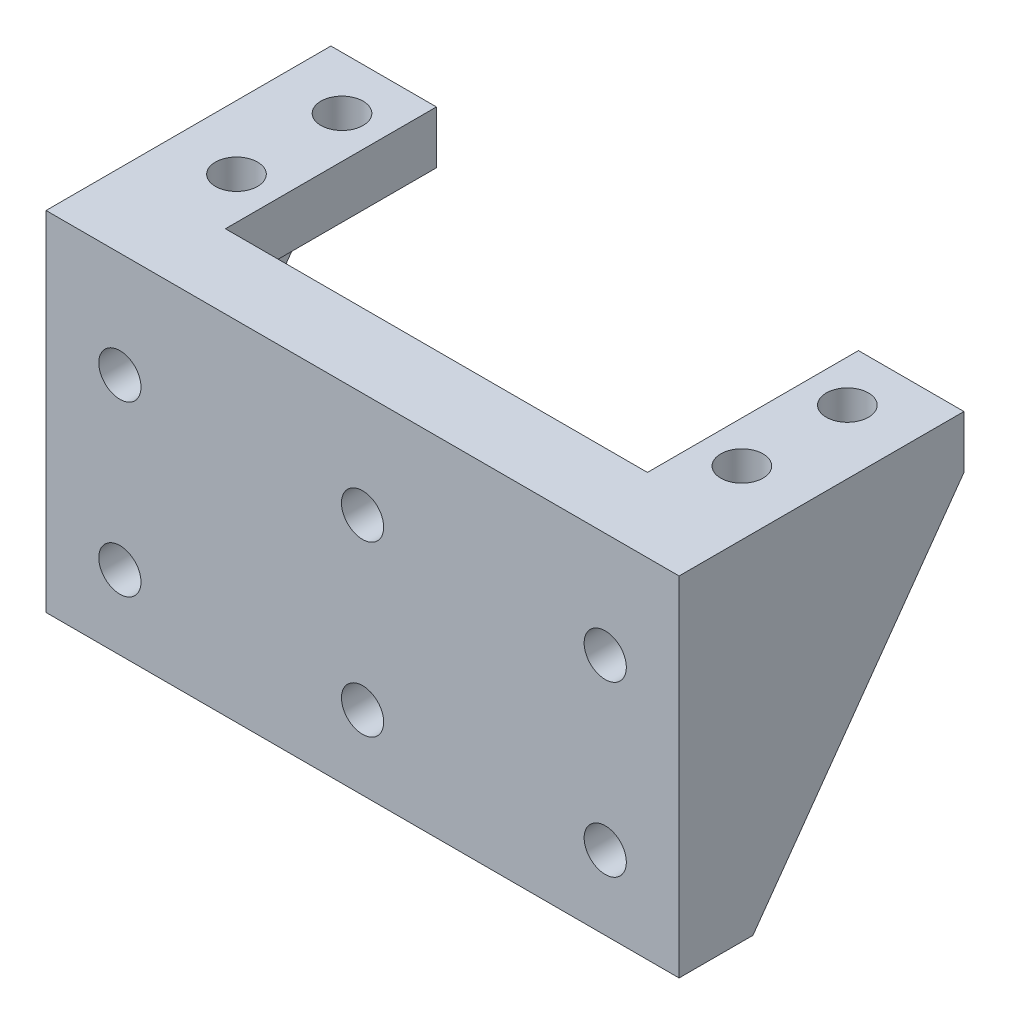
SolidWorks part; units mm, degrees
ref_plane "Front Plane" through (0, 0, 0) normal (0, 0, 1) x (1, 0, 0)
ref_plane "Top Plane" through (0, 0, 0) normal (0, 1, 0) x (1, 0, 0)
ref_plane "Right Plane" through (0, 0, 0) normal (1, 0, 0) x (0, 0, -1)
sketch "Sketch2" plane through (0, 0, 0) normal (0, 1, 0) x (1, 0, 0)
  line L1 (0, 0) -> (40, 0) construction
  line L2 (0, 0) -> (0, 20) construction
  line L3 (0, 20) -> (40, 20) construction
  line L4 (40, 0) -> (40, 20) construction
  line L5 (0, 20) -> (-8, 20)
  line L6 (0, 20) -> (0, 0)
  line L7 (0, 0) -> (-8, 0)
  line L8 (-8, 20) -> (-8, 0)
  line L9 (40, 0) -> (48, 0)
  line L10 (40, 0) -> (40, 20)
  line L11 (40, 20) -> (48, 20)
  line L12 (48, 0) -> (48, 20)
  line L13 (-8, 0) -> (48, 0)
  line L14 (-8, 0) -> (-8, -7)
  line L15 (-8, -7) -> (48, -7)
  line L16 (48, 0) -> (48, -7)
  line L17 (0, 0) -> (40, 0) construction
  line L18 (0, 0) -> (0, 20) construction
  line L19 (0, 20) -> (40, 20) construction
  line L20 (40, 0) -> (40, 20) construction
  line L21 (0, 0) -> (40, 20) construction
  line L22 (0, 20) -> (40, 0) construction
  line L23 (-8, -7) -> (3.75, -7)
  line L24 (-8, -7) -> (-8, -19.66)
  line L25 (-8, -19.66) -> (3.75, -19.66)
  line L26 (3.75, -7) -> (3.75, -19.66)
  line L27 (16.85, -7) -> (28.6, -7)
  line L28 (16.85, -7) -> (16.85, -19.66)
  line L29 (16.85, -19.66) -> (28.6, -19.66)
  line L30 (28.6, -7) -> (28.6, -19.66)
  point P8 (20, 10)
  dimension "D1" = 8
  dimension "D2" = 20
  dimension "D3" = 40
  dimension "D4" = 12.66
  dimension "D5" = 3.75
  dimension "D6" = 13.1
  dimension "D7" = 7
  dimension "D8" = 11.75
extrude "Boss-Extrude1" add sketch "Sketch2" along normal blind 5 contours L5 L8 L7 L6 | L16 L9 L13 L7 L14 L15 | L26 L15 L24 L25 | L30 L15 L28 L29 | L9 L12 L11 L10
sketch "Sketch3" plane through (0, 0, 0) normal (0, -1, 0) x (1, 0, 0)
  line L0 (0, 0) -> (40, 0) construction
  line L1 (-8, 19.66) -> (3.75, 19.66)
  line L2 (-8, 19.66) -> (-8, 0)
  line L3 (-8, 0) -> (3.75, 0)
  line L4 (3.75, 19.66) -> (3.75, 0)
  line L5 (28.6, 7) -> (28.6, 19.66) construction
  line L6 (16.85, 19.66) -> (28.6, 19.66)
  line L7 (16.85, 19.66) -> (16.85, 0)
  line L8 (16.85, 0) -> (28.6, 0)
  line L9 (28.6, 19.66) -> (28.6, 0)
  line L11 (3.75, 0) -> (16.85, 0)
  line L12 (3.75, 0) -> (3.75, 7)
  line L13 (3.75, 7) -> (16.85, 7)
  line L14 (16.85, 0) -> (16.85, 7)
  line M15 (0, 0) -> (40, 0)
  line M20 (28.6, 7) -> (28.6, 19.66)
  line M21 (28.6, 19.66) -> (16.85, 19.66)
  line M22 (16.85, 19.66) -> (16.85, 7)
  line M23 (16.85, 7) -> (3.75, 7)
  line M24 (3.75, 7) -> (3.75, 19.66)
  line M25 (3.75, 19.66) -> (-8, 19.66)
  line M26 (-8, 19.66) -> (-8, -20)
extrude "Boss-Extrude2" add sketch "Sketch3" along normal blind 28 contours L4 L3 M24 M25 M26 M15 | L7 L4 M23 M15 | L9 L7 M20 M21 M22 M15
sketch "Sketch4" plane through (0, -28, 0) normal (0, -1, 0) x (1, 0, 0)
  line L1 (-8, 19.66) -> (-2.25, 19.66)
  line L2 (-8, 19.66) -> (-8, 7)
  line L3 (-8, 7) -> (-2.25, 7)
  line L4 (-2.25, 19.66) -> (-2.25, 7)
  line L5 (28.6, 19.66) -> (22.85, 19.66)
  line L6 (28.6, 19.66) -> (28.6, 7)
  line L7 (28.6, 7) -> (22.85, 7)
  line L8 (22.85, 19.66) -> (22.85, 7)
  line L9 (3.75, 19.66) -> (3.75, 7) construction
  line L10 (16.85, 19.66) -> (16.85, 7) construction
  line L11 (16.85, 7) -> (3.75, 7) construction
  dimension "D1" = 6
  dimension "D2" = 6
extrude "Cut-Extrude1" cut sketch "Sketch4" against normal through all
sketch "Sketch5" plane through (-2.25, 0, 0) normal (-1, 0, 0) x (0, 0, 1)
  line L0 (13.33, 5) -> (13.33, -28) construction
  line L1 (7, 5) -> (19.66, 5) construction
  line L2 (7, -28) -> (19.66, -28) construction
  circle A0 centre (13.33, -2) radius 2
  circle A1 centre (13.33, -21) radius 2
  circle A2 centre (13.33, -11.5) radius 2
  dimension "D1" = 4
  dimension "D2" = 7
  dimension "D3" = 7
extrude "Cut-Extrude2" cut sketch "Sketch5" against normal through all
sketch "Sketch6" plane through (0, 0, 0) normal (0, -1, 0) x (1, 0, 0)
  line L0 (40, -10) -> (0, -10) construction
  line L1 (-3.95, -5) -> (43.95, -5) construction
  line L2 (-3.95, -5) -> (-3.95, -15) construction
  line L3 (-3.95, -15) -> (43.95, -15) construction
  line L4 (43.95, -5) -> (43.95, -15) construction
  line L5 (40, 0) -> (40, -20) construction
  line L6 (0, -20) -> (0, 0) construction
  line L7 (20, -10) -> (20, -15) construction
  line L8 (20, -10) -> (20, -5) construction
  circle A0 centre (43.95, -5) radius 2
  circle A1 centre (43.95, -15) radius 2
  circle A2 centre (-3.95, -5) radius 2
  circle A3 centre (-3.95, -15) radius 2
  dimension "D3" = 4
  dimension "D1" = 10
  dimension "D2" = 47.9
extrude "Cut-Extrude3" cut sketch "Sketch6" against normal through all contours A2
sketch "Sketch7" plane through (28.6, 0, 0) normal (1, 0, 0) x (0, 0, -1)
  line L4 (-7, 0) -> (-7, -28)
  line L5 (-7, -28) -> (0, -28)
  line L6 (0, -28) -> (0, 0)
  line L7 (0, 0) -> (-7, 0)
  line L8 (-7, 0) -> (-7, -28)
  line L9 (-7, -28) -> (0, -28)
  line L10 (0, -28) -> (0, 0)
  line L11 (0, 0) -> (-7, 0)
  dimension "D1" = 0
extrude "Boss-Extrude3" add sketch "Sketch7" along normal up to surface (19.4 mm away) up to face at (48, 2.5, -6.5)
sketch "Sketch8" plane through (48, 0, 0) normal (1, 0, 0) x (0, 0, -1)
  line L1 (-7, -28) -> (20, -28)
  line L2 (-7, -28) -> (-7, 5)
  line L3 (-7, 5) -> (20, 5)
  line L4 (20, -28) -> (20, 5)
extrude "Boss-Extrude4" add sketch "Sketch8" along normal blind 2
sketch "Sketch9" plane through (-8, 0, 0) normal (-1, 0, 0) x (0, 0, 1)
  line L1 (-20, 5) -> (7, 5)
  line L2 (-20, 5) -> (-20, -28)
  line L3 (-20, -28) -> (7, -28)
  line L4 (7, 5) -> (7, -28)
extrude "Boss-Extrude5" add sketch "Sketch9" along normal blind 2
sketch "Sketch10" plane through (48, 0, 0) normal (-1, 0, 0) x (0, 0, 1)
  line L0 (-20, 0) -> (0, -28)
  line L1 (0, -28) -> (-20, -28)
  line L2 (-20, -28) -> (-20, 0)
extrude "Cut-Extrude4" cut sketch "Sketch10" against normal through all and the other way through all
sketch "Sketch11" plane through (22.85, 0, 0) normal (1, 0, 0) x (0, 0, -1)
  line L1 (-19.66, -28) -> (-7, -28)
  line L2 (-19.66, -28) -> (-19.66, 5)
  line L3 (-19.66, 5) -> (-7, 5)
  line L4 (-7, -28) -> (-7, 5)
extrude "Cut-Extrude5" cut sketch "Sketch11" against normal through all
sketch "Sketch12" plane through (0, 0, 0) normal (0, 0, -1) x (-1, 0, 0)
  line L0 (8, -5) -> (-48, -5) construction
  line L1 (8, -28) -> (8, 0) construction
  line L2 (-48, -28) -> (-48, 0) construction
  line L3 (-48, 0) -> (-40, 0) construction
  line L4 (8, -21) -> (-48, -21) construction
  line L5 (3, -5) -> (3, -21) construction
  line L6 (-43, -5) -> (-43, -21) construction
  line L7 (8, -28) -> (-48, -28) construction
  circle A0 centre (-43, -5) radius 2
  circle A1 centre (3, -5) radius 2
  circle A2 centre (3, -21) radius 2
  circle A3 centre (-43, -21) radius 2
  circle A4 centre (-20, -5) radius 2
  circle A5 centre (-20, -21) radius 2
  point P20 (-48, -23)
  dimension "D2" = 4
  dimension "D1" = 5
  dimension "D3" = 5
  dimension "D4" = 5
  dimension "D5" = 7
extrude "Cut-Extrude6" cut sketch "Sketch12" against normal through all
sketch "Sketch13" plane through (0, 0, 0) normal (0, 0, -1) x (-1, 0, 0)
  circle A0 centre (-43, -5) radius 2 construction
  circle A1 centre (3, -5) radius 2 construction
  circle A2 centre (-43, -5) radius 2
  circle A3 centre (3, -5) radius 2
  circle A4 centre (3, -5) radius 4
  circle A5 centre (-43, -5) radius 4
  circle A6 centre (3, -21) radius 4
  circle A7 centre (-43, -21) radius 4
  circle A8 centre (-43, -21) radius 2 construction
  circle A9 centre (3, -21) radius 2 construction
  circle A10 centre (-20, -21) radius 4
  circle A11 centre (-20, -5) radius 4
  circle A12 centre (-20, -5) radius 2 construction
  circle A13 centre (-20, -21) radius 2 construction
  dimension "D1" = 8
extrude "Cut-Extrude7" cut sketch "Sketch13" against normal blind 2.8
